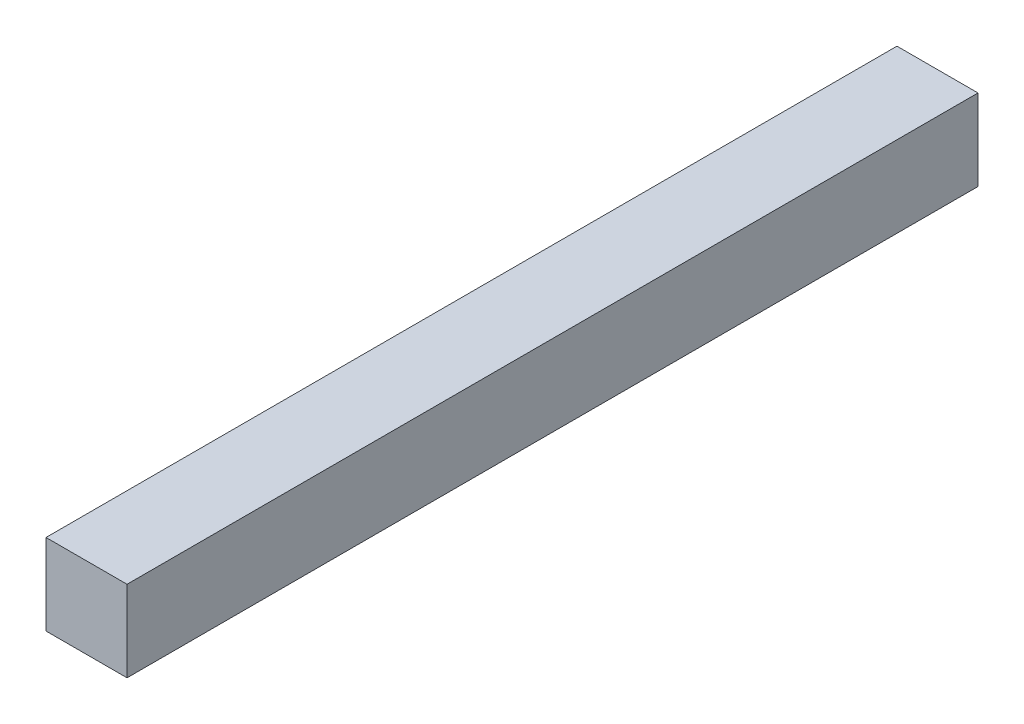
SolidWorks part; units mm, degrees
ref_plane "Front Plane" through (0, 0, 0) normal (0, 0, 1) x (1, 0, 0)
ref_plane "Top Plane" through (0, 0, 0) normal (0, 1, 0) x (1, 0, 0)
ref_plane "Right Plane" through (0, 0, 0) normal (1, 0, 0) x (0, 0, -1)
sketch "Sketch1" plane through (0, 0, 0) normal (0, 0, 1) x (1, 0, 0)
  line L1 (-275.0254, 93.8071) -> (-235.0254, 93.8071)
  line L2 (-275.0254, 93.8071) -> (-275.0254, 53.8071)
  line L3 (-275.0254, 53.8071) -> (-235.0254, 53.8071)
  line L4 (-235.0254, 93.8071) -> (-235.0254, 53.8071)
  dimension "D1" = 40
  dimension "D2" = 40
extrude "Boss-Extrude1" add sketch "Sketch1" along normal blind 420
